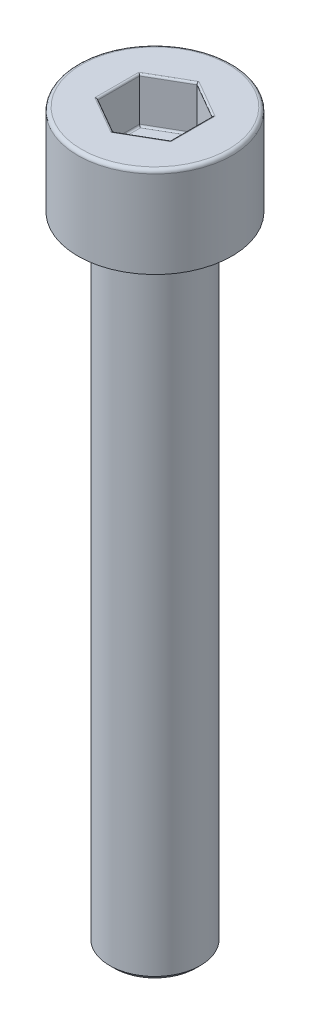
SolidWorks part; units mm, degrees
ref_plane "Front Plane" through (0, 0, 0) normal (0, 0, 1) x (1, 0, 0)
ref_plane "Top Plane" through (0, 0, 0) normal (0, 1, 0) x (1, 0, 0)
ref_plane "Right Plane" through (0, 0, 0) normal (1, 0, 0) x (0, 0, -1)
sketch "Sketch1" plane through (0, 0, 0) normal (0, 0, 1) x (1, 0, 0)
  line L0 (0, 0) -> (0, -47.0967) construction
  line L1 (0, -40) -> (-2.5, -40)
  line L2 (-2.5, -40) -> (-2.5, -5)
  line L3 (-2.5, -5) -> (-4.25, -5)
  line L4 (-4.25, -5) -> (-4.25, 0)
  line L5 (-4.25, 0) -> (0, 0)
  line L6 (0, 0) -> (0, -40)
  dimension "d" = 5
  dimension "l" = 40
  dimension "k" = 5
  dimension "dk" = 8.5
revolve "Revolve1" add sketch "Sketch1" angle 360 about L0
chamfer "Chamfer1" distance 0.25 angle 45 2 edges at (0, -5, 2.5) (0, -40, 2.5)
fillet "Fillet1" radius 0.2 1 edges at (0, 0, 4.25)
sketch "Sketch2" plane through (0, 0, 0) normal (0, 1, 0) x (1, 0, 0)
  line L1 (0, 2.3094) -> (-2, 1.1547)
  line L2 (-2, 1.1547) -> (-2, -1.1547)
  line L3 (-2, -1.1547) -> (0, -2.3094)
  line L4 (0, -2.3094) -> (2, -1.1547)
  line L5 (2, -1.1547) -> (2, 1.1547)
  line L6 (2, 1.1547) -> (0, 2.3094)
  circle A0 centre (0, 0) radius 2 construction
  dimension "s" = 4
extrude "Cut-Extrude1" cut sketch "Sketch2" against normal blind 2.5
fillet "Fillet2" radius 0.1 12 edges at (-1, 0, -1.7321) (-2, 0, 0) (-1, 0, 1.7321) (1, 0, 1.7321) (2, 0, 0) (1, 0, -1.7321) (2, -2.5, 0) (1, -2.5, 1.7321) (-1, -2.5, 1.7321) (-2, -2.5, 0) (-1, -2.5, -1.7321) (1, -2.5, -1.7321)
